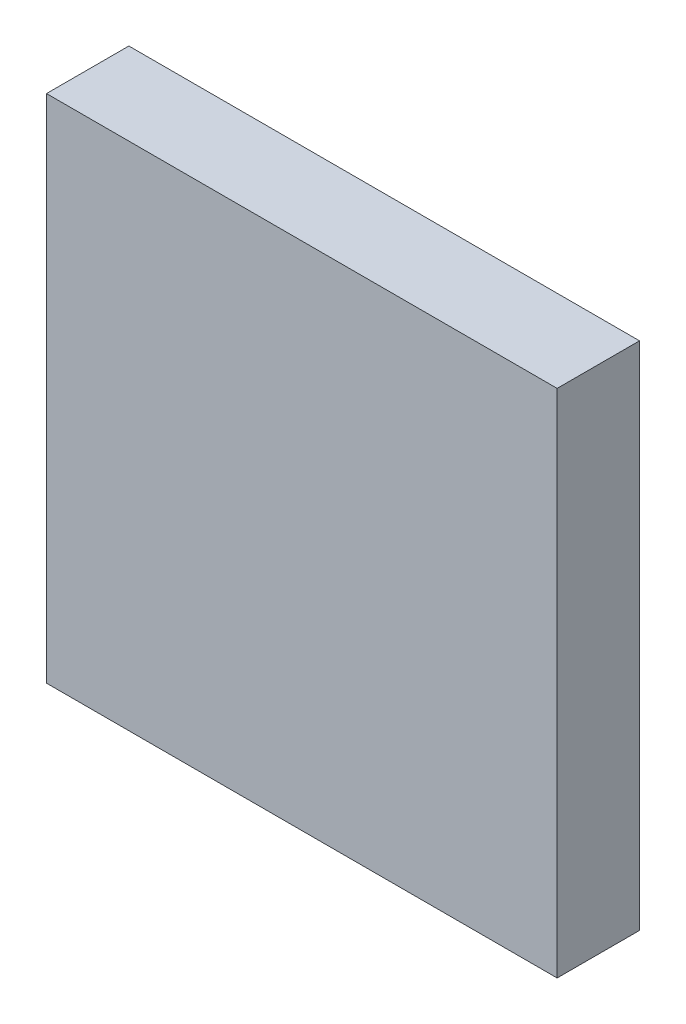
SolidWorks part; units mm, degrees
ref_plane "Спереди" through (0, 0, 0) normal (0, 0, 1) x (1, 0, 0)
ref_plane "Сверху" through (0, 0, 0) normal (0, 1, 0) x (1, 0, 0)
ref_plane "Справа" through (0, 0, 0) normal (1, 0, 0) x (0, 0, -1)
sketch "Эскиз5" plane through (0, 0, 0) normal (0, 0, 1) x (1, 0, 0)
  line L1 (-31, -31) -> (31, -31)
  line L2 (-31, -31) -> (-31, 31)
  line L3 (-31, 31) -> (31, 31)
  line L4 (31, -31) -> (31, 31)
  line L5 (-31, -31) -> (31, 31) construction
  line L6 (-31, 31) -> (31, -31) construction
  point P0 (0, 0)
extrude "Бобышка-Вытянуть2" add sketch "Эскиз5" along normal blind 10 contours L2 L3 L4 L1
sketch "Эскиз13" plane through (0, 0, 10) normal (0, 0, 1) x (1, 0, 0)
  line L3 (-3.8388, 8.5) -> (2.9703, 8.5)
  line L4 (2.9278, -8.5) -> (-3.8388, -8.5)
  spline S0 degree 3 poles (6.2881, 3.7602) (5.7125, 4.1456) (5.3316, 4.7609) (5.2431, 5.448) knots 0 0 0 0 0.333333 0.333333 0.333333 0.333333
  spline S1 degree 3 poles (5.2431, 5.448) (5.1547, 6.135) (5.3675, 6.8268) (5.8267, 7.3454) knots 0.333333 0.333333 0.333333 0.333333 1 1 1 1
  spline S2 degree 3 poles (-4.2595, 8.2703) (-4.1675, 8.4134) (-4.009, 8.5) (-3.8388, 8.5) knots 0 0 0 0 1 1 1 1
  spline S3 degree 3 poles (-4.2595, -8.2703) (-7.4966, -3.2319) (-7.4966, 3.2319) (-4.2595, 8.2703) knots 0 0 0 0 1 1 1 1
  spline S4 degree 3 poles (-3.8388, -8.5) (-4.009, -8.5) (-4.1675, -8.4134) (-4.2595, -8.2703) knots 0 0 0 0 1 1 1 1
  spline S5 degree 3 poles (4.0581, 8.9672) (3.7749, 8.6689) (3.3816, 8.5) (2.9703, 8.5) knots 0 0 0 0 1 1 1 1
  spline S6 degree 3 poles (4.0581, 8.9672) (4.5088, 9.4419) (5.2568, 9.4678) (5.7393, 9.0253) knots 0 0 0 0 0.333333 0.333333 0.333333 0.333333
  spline S7 degree 3 poles (5.7393, 9.0253) (6.2218, 8.5829) (6.2607, 7.8355) (5.8267, 7.3454) knots 0.333333 0.333333 0.333333 0.333333 1 1 1 1
  spline S8 degree 3 poles (2.9278, -8.5) (3.3579, -8.5) (3.77, -8.6732) (4.0709, -8.9805) knots 0 0 0 0 1 1 1 1
  spline S9 degree 3 poles (6.0438, -7.6987) (5.5547, -6.4648) (5.6352, -5.0779) (6.2639, -3.9089) knots 0 0 0 0 1 1 1 1
  spline S10 degree 3 poles (6.0438, -7.6987) (6.2544, -8.2299) (6.0612, -8.8358) (5.5821, -9.1472) knots 0 0 0 0 0.333333 0.333333 0.333333 0.333333
  spline S11 degree 3 poles (5.5821, -9.1472) (5.1029, -9.4585) (4.4707, -9.3888) (4.0709, -8.9805) knots 0.333333 0.333333 0.333333 0.333333 1 1 1 1
  spline S12 degree 3 poles (6.3186, -3.1792) (5.6394, -1.2825) (5.741, 0.8063) (6.6012, 2.6281) knots 0 0 0 0 1 1 1 1
  spline S13 degree 3 poles (6.2881, 3.7602) (6.6582, 3.5123) (6.7914, 3.0309) (6.6012, 2.6281) knots 0 0 0 0 1 1 1 1
  spline S14 degree 3 poles (6.3186, -3.1792) (6.4045, -3.4192) (6.3847, -3.6844) (6.2639, -3.9089) knots 0 0 0 0 1 1 1 1
sketch "остров" plane through (0, 0, 10) normal (0, 0, 1) x (1, 0, 0)
  spline S40 degree 3 poles (-5.7898, -5.6368) (-5.8728, -5.6949) (-5.9715, -5.7264) (-6.0728, -5.7271) knots 0 0 0 0 1 1 1 1
  spline S41 degree 3 poles (5.4083, -5.2485) (5.2964, -5.2648) (5.1822, -5.2427) (5.0845, -5.1857) knots 0 0 0 0 1 1 1 1
  spline S42 degree 3 poles (3.7602, -6.288) (4.1382, -5.7235) (4.7372, -5.3463) (5.4083, -5.2484) knots 0 0 0 0 0.3269 0.3269 0.3269 0.3269
  spline S47 degree 3 poles (-5.7898, -5.6368) (-2.563, -3.3793) (1.6818, -3.2032) (5.0845, -5.1857) knots 0 0 0 0 1 1 1 1
  spline S52 degree 3 poles (-6.0728, -5.7271) (-5.3265, -5.7218) (-4.5816, -5.902) (-3.9089, -6.2638) knots 0.424548 0.424548 0.424548 0.424548 1 1 1 1
  spline S55 degree 3 poles (-3.1792, -6.3185) (-1.2825, -5.6393) (0.8063, -5.7409) (2.6281, -6.6011) knots 0 0 0 0 1 1 1 1
  spline S56 degree 3 poles (3.7602, -6.288) (3.5123, -6.6581) (3.0309, -6.7913) (2.6281, -6.6011) knots 0 0 0 0 1 1 1 1
  spline S57 degree 3 poles (-3.1792, -6.3185) (-3.4192, -6.4044) (-3.6844, -6.3846) (-3.9089, -6.2638) knots 0 0 0 0 1 1 1 1
sketch "карман под съем моста" plane through (0, 0, 10) normal (0, 0, 1) x (1, 0, 0)
  line L0 (-13.7619, 0) -> (13.4181, 0) construction
  line L1 (-13.7619, 1) -> (13.4181, 1)
  line L2 (-13.7619, -1) -> (13.4181, -1)
  arc A0 (-13.7619, 1) -> (-13.7619, -1) centre (-13.7619, 0) ccw
  arc A1 (13.4181, -1) -> (13.4181, 1) centre (13.4181, 0) ccw
  point P3 (-0.1719, 0)
sketch "уголки" plane through (0, 0, 10) normal (0, 0, 1) x (1, 0, 0)
  spline S0 degree 2 poles (2.0317, 8.5) (2.5998, 8.5) (2.9703, 8.5) knots 0 0 0 1 1 1
  spline S1 degree 3 poles (-5.3435, 5.4691) (-5.5492, 5.4628) (-5.73, 5.3311) (-5.7991, 5.1372) knots 0 0 0 0 1 1 1 1
  spline S2 degree 3 poles (-4.2129, 8.3317) (-4.2866, 8.1698) (-4.2686, 7.9808) (-4.1657, 7.8357) knots 0 0 0 0 1 1 1 1
  spline S3 degree 3 poles (-4.2129, 8.3317) (-4.2298, 8.3126) (-4.2455, 8.2921) (-4.2595, 8.2703) knots 0 0 0 0 1 1 1 1
  spline S4 degree 3 poles (2.5311, 8.0243) (2.5182, 8.2907) (2.2984, 8.5) (2.0317, 8.5) knots 0 0 0 0 1 1 1 1
  spline S5 degree 3 poles (2.5311, 8.0243) (2.5908, 6.7965) (3.5687, 5.8123) (4.7961, 5.7445) knots 0 0 0 0 1 1 1 1
  spline S6 degree 3 poles (5.2608, 5.3331) (5.2201, 5.5614) (5.0277, 5.7318) (4.7961, 5.7445) knots 0 0 0 0 1 1 1 1
  spline S7 degree 3 poles (5.7438, -6.4277) (5.781, -6.8591) (5.8808, -7.2875) (6.0438, -7.6987) knots 0 0 0 0 1 1 1 1
  spline S8 degree 3 poles (5.1523, -6.962) (5.3061, -6.9912) (5.4647, -6.9468) (5.5808, -6.8418) knots 0 0 0 0 0.333333 0.333333 0.333333 0.333333
  spline S9 degree 3 poles (5.5808, -6.8418) (5.697, -6.7369) (5.7573, -6.5837) (5.7438, -6.4277) knots 0.333333 0.333333 0.333333 0.333333 1 1 1 1
  spline S10 degree 3 poles (5.1523, -6.962) (4.8155, -6.898) (4.4674, -6.9811) (4.1958, -7.1904) knots 0 0 0 0 0.333333 0.333333 0.333333 0.333333
  spline S11 degree 3 poles (4.1958, -7.1904) (3.9242, -7.3997) (3.7551, -7.7151) (3.7312, -8.0571) knots 0.333333 0.333333 0.333333 0.333333 1 1 1 1
  spline S12 degree 3 poles (3.1599, -8.5169) (3.2976, -8.5371) (3.4375, -8.499) (3.5459, -8.4117) knots 0 0 0 0 0.333333 0.333333 0.333333 0.333333
  spline S13 degree 3 poles (3.5459, -8.4117) (3.6543, -8.3245) (3.7215, -8.196) (3.7312, -8.0571) knots 0.333333 0.333333 0.333333 0.333333 1 1 1 1
  spline S14 degree 3 poles (4.0709, -8.9805) (3.8247, -8.729) (3.504, -8.5673) (3.1599, -8.5169) knots 0 0 0 0 1 1 1 1
  spline S15 degree 3 poles (-4.2595, -8.2703) (-4.2455, -8.2921) (-4.2298, -8.3126) (-4.2129, -8.3317) knots 0 0 0 0 1 1 1 1
  spline S16 degree 3 poles (-4.1657, -7.8357) (-4.2686, -7.9808) (-4.2866, -8.1698) (-4.2129, -8.3317) knots 0 0 0 0 1 1 1 1
  spline S17 degree 3 poles (-4.1657, -7.8357) (-3.8462, -7.3848) (-3.8005, -6.7948) (-4.0467, -6.3001) knots 0 0 0 0 0.333333 0.333333 0.333333 0.333333
  spline S18 degree 3 poles (-4.0467, -6.3001) (-4.2929, -5.8054) (-4.7912, -5.4861) (-5.3435, -5.4691) knots 0.333333 0.333333 0.333333 0.333333 1 1 1 1
  spline S19 degree 3 poles (-5.7991, -5.1372) (-5.73, -5.3311) (-5.5492, -5.4628) (-5.3435, -5.4691) knots 0 0 0 0 1 1 1 1
  spline S20 degree 3 poles (-4.2595, 8.2703) (-4.8994, 7.2743) (-5.4129, 6.2227) (-5.7991, 5.1372) knots 0 0 0 0 1 1 1 1
  spline S21 degree 3 poles (-5.7991, -5.1372) (-5.4129, -6.2227) (-4.8994, -7.2744) (-4.2595, -8.2703) knots 0 0 0 0 1 1 1 1
  spline S22 degree 3 poles (5.8267, 7.3454) (5.3675, 6.8268) (5.1547, 6.135) (5.2431, 5.448) knots 0 0 0 0 0.333333 0.333333 0.333333 0.333333
  spline S23 degree 3 poles (5.2431, 5.448) (5.2481, 5.4095) (5.254, 5.3711) (5.2608, 5.3331) knots 0.333333 0.333333 0.333333 0.333333 1 1 1 1
  spline S24 degree 3 poles (-5.3435, 5.4691) (-4.7912, 5.4861) (-4.2929, 5.8054) (-4.0467, 6.3001) knots 0 0 0 0 0.333333 0.333333 0.333333 0.333333
  spline S25 degree 3 poles (-4.0467, 6.3001) (-3.8005, 6.7948) (-3.8462, 7.3848) (-4.1657, 7.8357) knots 0.333333 0.333333 0.333333 0.333333 1 1 1 1
  spline S26 degree 3 poles (2.9703, 8.5) (3.3816, 8.5) (3.7749, 8.6689) (4.0581, 8.9672) knots 0 0 0 0 1 1 1 1
  spline S27 degree 3 poles (4.0709, -8.9805) (4.4707, -9.3888) (5.1029, -9.4585) (5.5821, -9.1472) knots 0 0 0 0 0.333333 0.333333 0.333333 0.333333
  spline S28 degree 3 poles (5.5821, -9.1472) (6.0612, -8.8358) (6.2544, -8.2299) (6.0438, -7.6987) knots 0.333333 0.333333 0.333333 0.333333 1 1 1 1
  spline S29 degree 3 poles (5.8267, 7.3454) (6.2607, 7.8355) (6.2218, 8.5829) (5.7393, 9.0253) knots 0 0 0 0 0.333333 0.333333 0.333333 0.333333
  spline S30 degree 3 poles (5.7393, 9.0253) (5.2568, 9.4678) (4.5088, 9.4419) (4.0581, 8.9672) knots 0.333333 0.333333 0.333333 0.333333 1 1 1 1
sketch "перлаж сетка" plane through (0, 0, 10) normal (0, 0, 1) x (1, 0, 0)
  circle A0 centre (-3.678, -8.077) radius 1
  circle A1 centre (-4.2433, -7.0322) radius 1
  circle A2 centre (-4.729, -5.9482) radius 1
  circle A3 centre (-5.1324, -4.8308) radius 1
  circle A4 centre (-5.451, -3.6865) radius 1
  circle A5 centre (-5.6833, -2.5215) radius 1
  circle A6 centre (-5.8279, -1.3425) radius 1
  circle A7 centre (-5.884, -0.1559) radius 1
  circle A8 centre (-5.8512, 1.0316) radius 1
  circle A9 centre (-5.7298, 2.2132) radius 1
  circle A10 centre (-5.5204, 3.3825) radius 1
  circle A11 centre (-5.2242, 4.5329) radius 1
  circle A12 centre (-4.8429, 5.658) radius 1
  circle A13 centre (-4.3786, 6.7514) radius 1
  circle A14 centre (-3.8339, 7.807) radius 1
  circle A15 centre (-2.478, -8.077) radius 1
  circle A16 centre (-3.0433, -7.0322) radius 1
  circle A17 centre (-3.529, -5.9482) radius 1
  circle A18 centre (-3.9324, -4.8308) radius 1
  circle A19 centre (-4.251, -3.6865) radius 1
  circle A20 centre (-4.4833, -2.5215) radius 1
  circle A21 centre (-4.6279, -1.3425) radius 1
  circle A22 centre (-4.684, -0.1559) radius 1
  circle A23 centre (-4.6512, 1.0316) radius 1
  circle A24 centre (-4.5298, 2.2132) radius 1
  circle A25 centre (-4.3204, 3.3825) radius 1
  circle A26 centre (-4.0242, 4.5329) radius 1
  circle A27 centre (-3.6429, 5.658) radius 1
  circle A28 centre (-3.1786, 6.7514) radius 1
  circle A29 centre (-2.6339, 7.807) radius 1
  circle A30 centre (-1.278, -8.077) radius 1
  circle A31 centre (-1.8433, -7.0322) radius 1
  circle A32 centre (-2.329, -5.9482) radius 1
  circle A33 centre (-2.7324, -4.8308) radius 1
  circle A34 centre (-3.051, -3.6865) radius 1
  circle A35 centre (-3.2833, -2.5215) radius 1
  circle A36 centre (-3.4279, -1.3425) radius 1
  circle A37 centre (-3.484, -0.1559) radius 1
  circle A38 centre (-3.4512, 1.0316) radius 1
  circle A39 centre (-3.3298, 2.2132) radius 1
  circle A40 centre (-3.1204, 3.3825) radius 1
  circle A41 centre (-2.8242, 4.5329) radius 1
  circle A42 centre (-2.4429, 5.658) radius 1
  circle A43 centre (-1.9786, 6.7514) radius 1
  circle A44 centre (-1.4339, 7.807) radius 1
  circle A45 centre (-0.078, -8.077) radius 1
  circle A46 centre (-0.6433, -7.0322) radius 1
  circle A47 centre (-1.129, -5.9482) radius 1
  circle A48 centre (-1.5324, -4.8308) radius 1
  circle A49 centre (-1.851, -3.6865) radius 1
  circle A50 centre (-2.0833, -2.5215) radius 1
  circle A51 centre (-2.2279, -1.3425) radius 1
  circle A52 centre (-2.284, -0.1559) radius 1
  circle A53 centre (-2.2512, 1.0316) radius 1
  circle A54 centre (-2.1298, 2.2132) radius 1
  circle A55 centre (-1.9204, 3.3825) radius 1
  circle A56 centre (-1.6242, 4.5329) radius 1
  circle A57 centre (-1.2429, 5.658) radius 1
  circle A58 centre (-0.7786, 6.7514) radius 1
  circle A59 centre (-0.2339, 7.807) radius 1
  circle A60 centre (1.122, -8.077) radius 1
  circle A61 centre (0.5567, -7.0322) radius 1
  circle A62 centre (0.071, -5.9482) radius 1
  circle A63 centre (-0.3324, -4.8308) radius 1
  circle A64 centre (-0.651, -3.6865) radius 1
  circle A65 centre (-0.8833, -2.5215) radius 1
  circle A66 centre (-1.0279, -1.3425) radius 1
  circle A67 centre (-1.084, -0.1559) radius 1
  circle A68 centre (-1.0512, 1.0316) radius 1
  circle A69 centre (-0.9298, 2.2132) radius 1
  circle A70 centre (-0.7204, 3.3825) radius 1
  circle A71 centre (-0.4242, 4.5329) radius 1
  circle A72 centre (-0.0429, 5.658) radius 1
  circle A73 centre (0.4214, 6.7514) radius 1
  circle A74 centre (0.9661, 7.807) radius 1
  circle A75 centre (2.322, -8.077) radius 1
  circle A76 centre (1.7567, -7.0322) radius 1
  circle A77 centre (1.271, -5.9482) radius 1
  circle A78 centre (0.8676, -4.8308) radius 1
  circle A79 centre (0.549, -3.6865) radius 1
  circle A80 centre (0.3167, -2.5215) radius 1
  circle A81 centre (0.1721, -1.3425) radius 1
  circle A82 centre (0.116, -0.1559) radius 1
  circle A83 centre (0.1488, 1.0316) radius 1
  circle A84 centre (0.2702, 2.2132) radius 1
  circle A85 centre (0.4796, 3.3825) radius 1
  circle A86 centre (0.7758, 4.5329) radius 1
  circle A87 centre (1.1571, 5.658) radius 1
  circle A88 centre (1.6214, 6.7514) radius 1
  circle A89 centre (2.1661, 7.807) radius 1
  circle A90 centre (3.522, -8.077) radius 1
  circle A91 centre (2.9567, -7.0322) radius 1
  circle A92 centre (2.471, -5.9482) radius 1
  circle A93 centre (2.0676, -4.8308) radius 1
  circle A94 centre (1.749, -3.6865) radius 1
  circle A95 centre (1.5167, -2.5215) radius 1
  circle A96 centre (1.3721, -1.3425) radius 1
  circle A97 centre (1.316, -0.1559) radius 1
  circle A98 centre (1.3488, 1.0316) radius 1
  circle A99 centre (1.4702, 2.2132) radius 1
  circle A100 centre (1.6796, 3.3825) radius 1
  circle A101 centre (1.9758, 4.5329) radius 1
  circle A102 centre (2.3571, 5.658) radius 1
  circle A103 centre (2.8214, 6.7514) radius 1
  circle A104 centre (3.3661, 7.807) radius 1
  circle A105 centre (4.722, -8.077) radius 1
  circle A106 centre (4.1567, -7.0322) radius 1
  circle A107 centre (3.671, -5.9482) radius 1
  circle A108 centre (3.2676, -4.8308) radius 1
  circle A109 centre (2.949, -3.6865) radius 1
  circle A110 centre (2.7167, -2.5215) radius 1
  circle A111 centre (2.5721, -1.3425) radius 1
  circle A112 centre (2.516, -0.1559) radius 1
  circle A113 centre (2.5488, 1.0316) radius 1
  circle A114 centre (2.6702, 2.2132) radius 1
  circle A115 centre (2.8796, 3.3825) radius 1
  circle A116 centre (3.1758, 4.5329) radius 1
  circle A117 centre (3.5571, 5.658) radius 1
  circle A118 centre (4.0214, 6.7514) radius 1
  circle A119 centre (4.5661, 7.807) radius 1
  circle A120 centre (5.922, -8.077) radius 1
  circle A121 centre (5.3567, -7.0322) radius 1
  circle A122 centre (4.871, -5.9482) radius 1
  circle A123 centre (4.4676, -4.8308) radius 1
  circle A124 centre (4.149, -3.6865) radius 1
  circle A125 centre (3.9167, -2.5215) radius 1
  circle A126 centre (3.7721, -1.3425) radius 1
  circle A127 centre (3.716, -0.1559) radius 1
  circle A128 centre (3.7488, 1.0316) radius 1
  circle A129 centre (3.8702, 2.2132) radius 1
  circle A130 centre (4.0796, 3.3825) radius 1
  circle A131 centre (4.3758, 4.5329) radius 1
  circle A132 centre (4.7571, 5.658) radius 1
  circle A133 centre (5.2214, 6.7514) radius 1
  circle A134 centre (5.7661, 7.807) radius 1
  circle A135 centre (7.122, -8.077) radius 1
  circle A136 centre (6.5567, -7.0322) radius 1
  circle A137 centre (6.071, -5.9482) radius 1
  circle A138 centre (5.6676, -4.8308) radius 1
  circle A139 centre (5.349, -3.6865) radius 1
  circle A140 centre (5.1167, -2.5215) radius 1
  circle A141 centre (4.9721, -1.3425) radius 1
  circle A142 centre (4.916, -0.1559) radius 1
  circle A143 centre (4.9488, 1.0316) radius 1
  circle A144 centre (5.0702, 2.2132) radius 1
  circle A145 centre (5.2796, 3.3825) radius 1
  circle A146 centre (5.5758, 4.5329) radius 1
  circle A147 centre (5.9571, 5.658) radius 1
  circle A148 centre (6.4214, 6.7514) radius 1
  circle A149 centre (6.9661, 7.807) radius 1
  circle A150 centre (8.322, -8.077) radius 1
  circle A151 centre (7.7567, -7.0322) radius 1
  circle A152 centre (7.271, -5.9482) radius 1
  circle A153 centre (6.8676, -4.8308) radius 1
  circle A154 centre (6.549, -3.6865) radius 1
  circle A155 centre (6.3167, -2.5215) radius 1
  circle A156 centre (6.1721, -1.3425) radius 1
  circle A157 centre (6.116, -0.1559) radius 1
  circle A158 centre (6.1488, 1.0316) radius 1
  circle A159 centre (6.2702, 2.2132) radius 1
  circle A160 centre (6.4796, 3.3825) radius 1
  circle A161 centre (6.7758, 4.5329) radius 1
  circle A162 centre (7.1571, 5.658) radius 1
  circle A163 centre (7.6214, 6.7514) radius 1
  circle A164 centre (8.1661, 7.807) radius 1
  point P33 (10, 0)
  dimension "D1" = 15
  dimension "D2" = 11
